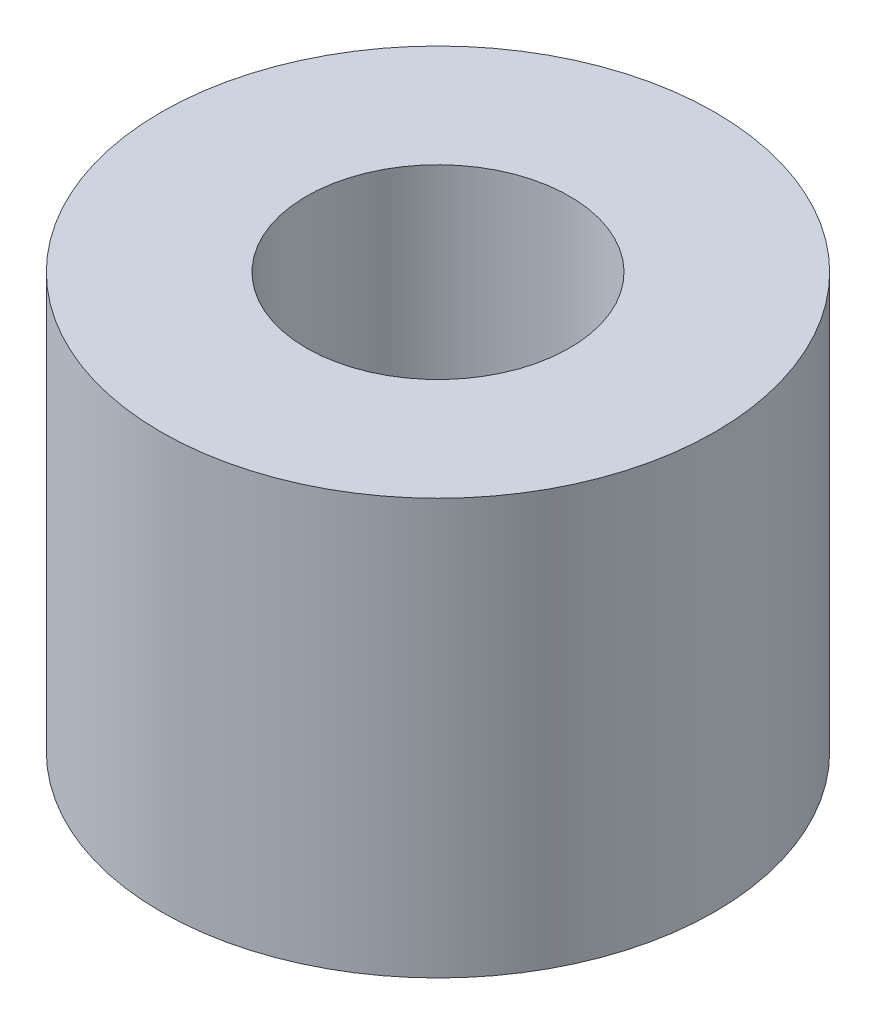
SolidWorks part; units mm, degrees
ref_plane "Plano frontal" through (0, 0, 0) normal (0, 0, 1) x (1, 0, 0)
ref_plane "Plano superior" through (0, 0, 0) normal (0, 1, 0) x (1, 0, 0)
ref_plane "Plano direito" through (0, 0, 0) normal (1, 0, 0) x (0, 0, -1)
sketch "Esboço1" plane through (0, 0, 0) normal (0, 1, 0) x (1, 0, 0)
  circle A0 centre (0, 0) radius 2
  circle A1 centre (0, 0) radius 0.95
  dimension "D1" = 4
  dimension "D2" = 1.9
extrude "Ressalto-extrusão1" add sketch "Esboço1" along normal blind 3
